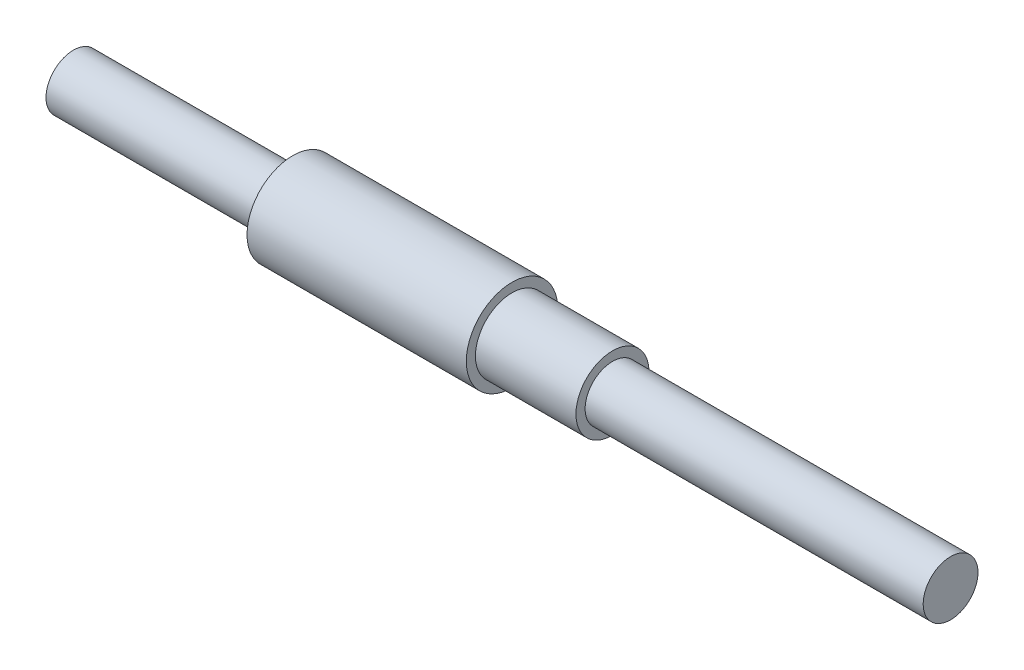
SolidWorks part; units mm, degrees
ref_plane "前视基准面" through (0, 0, 0) normal (0, 0, 1) x (1, 0, 0)
ref_plane "上视基准面" through (0, 0, 0) normal (0, 1, 0) x (1, 0, 0)
ref_plane "右视基准面" through (0, 0, 0) normal (1, 0, 0) x (0, 0, -1)
sketch "草图1" plane through (0, 0, 0) normal (1, 0, 0) x (0, 0, -1)
  circle A0 centre (0, 0) radius 1.5
extrude "凸台-拉伸1" add sketch "草图1" along normal blind 48
sketch "草图2" plane through (0, 0, 0) normal (-1, 0, 0) x (0, 0, 1)
  circle A0 centre (0, 0) radius 2.5
  circle A1 centre (0, 0) radius 1.5
sketch "草图3" plane through (0, 0, 0) normal (1, 0, 0) x (0, 0, -1)
  circle A0 centre (0, 0) radius 2
  circle A1 centre (0, 0) radius 1.5
extrude "凸台-拉伸2" add sketch "草图2" against normal blind 12 from offset 12 offset against normal yes
extrude "凸台-拉伸3" add sketch "草图3" along normal blind 5.5 from surface at 24 starting at face at (24, 0, 1.5)
